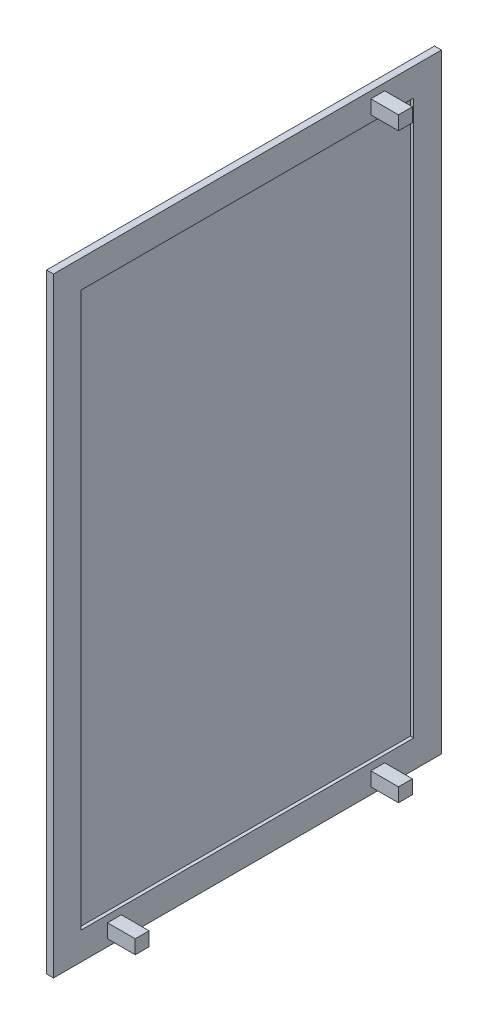
SolidWorks part; units mm, degrees
ref_plane "Front Plane" through (0, 0, 0) normal (0, 0, 1) x (1, 0, 0)
ref_plane "Top Plane" through (0, 0, 0) normal (0, 1, 0) x (1, 0, 0)
ref_plane "Right Plane" through (0, 0, 0) normal (1, 0, 0) x (0, 0, -1)
sketch "Sketch1" plane through (0, 0, 0) normal (1, 0, 0) x (0, 0, -1)
  line L1 (0, 0) -> (70, 0)
  line L2 (0, 0) -> (0, 110)
  line L3 (0, 110) -> (70, 110)
  line L4 (70, 0) -> (70, 110)
  dimension "D1" = 110
  dimension "D2" = 70
extrude "Boss-Extrude1" add sketch "Sketch1" along normal blind 1.25
sketch "Sketch2" plane through (1.25, 0, 0) normal (1, 0, 0) x (0, 0, -1)
  line L1 (57.25, 108.75) -> (59.75, 108.75)
  line L2 (57.25, 108.75) -> (57.25, 106.25)
  line L3 (57.25, 106.25) -> (59.75, 106.25)
  line L4 (59.75, 108.75) -> (59.75, 106.25)
  line L5 (70, 110) -> (0, 110) construction
  line L6 (0, 0) -> (70, 0) construction
  line L7 (9.75, 3.75) -> (12.25, 3.75)
  line L8 (9.75, 3.75) -> (9.75, 1.25)
  line L9 (9.75, 1.25) -> (12.25, 1.25)
  line L10 (12.25, 3.75) -> (12.25, 1.25)
  line L12 (57.25, 3.75) -> (59.75, 3.75)
  line L13 (57.25, 3.75) -> (57.25, 1.25)
  line L14 (57.25, 1.25) -> (59.75, 1.25)
  line L15 (59.75, 3.75) -> (59.75, 1.25)
  line L16 (70, 0) -> (70, 110) construction
  dimension "D1" = 2.5
  dimension "D2" = 2.5
  dimension "D3" = 10.25
  dimension "D4" = 1.25
  dimension "D5" = 2.5
  dimension "D6" = 2.5
  dimension "D7" = 10.25
  dimension "D8" = 1.25
  dimension "D9" = 2.5
  dimension "D10" = 2.5
  dimension "D11" = 1.25
  dimension "D12" = 45
extrude "Boss-Extrude2" add sketch "Sketch2" along normal blind 5
sketch "Sketch3" plane through (1.25, 0, 0) normal (1, 0, 0) x (0, 0, -1)
  line L0 (0, 110) -> (0, 0) construction
  line L1 (5, 105) -> (65, 105)
  line L2 (5, 105) -> (5, 5)
  line L3 (5, 5) -> (65, 5)
  line L4 (65, 105) -> (65, 5)
  line L5 (70, 110) -> (0, 110) construction
  line L6 (70, 0) -> (70, 110) construction
  line L7 (0, 0) -> (70, 0) construction
  dimension "D1" = 5
  dimension "D2" = 5
  dimension "D3" = 5
  dimension "D4" = 5
extrude "Cut-Extrude1" cut sketch "Sketch3" against normal blind 0.6
